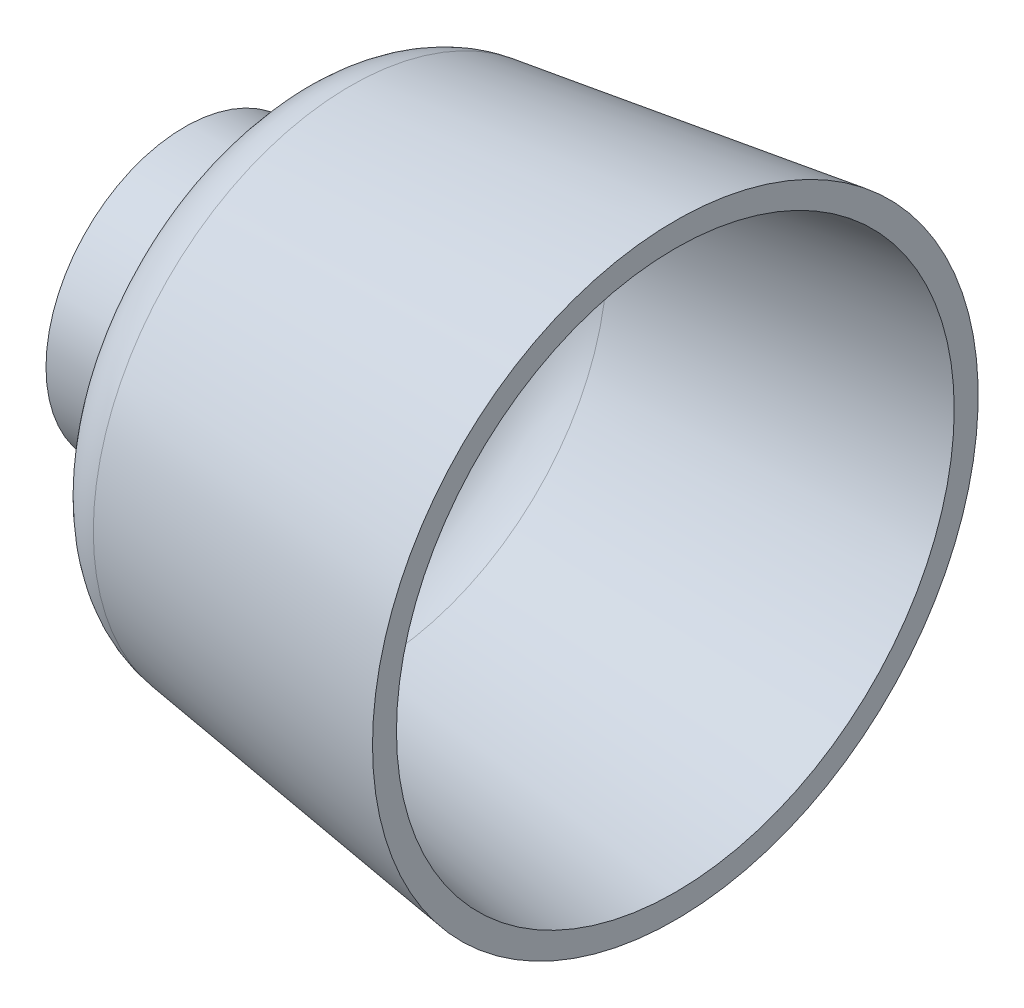
SolidWorks part; units mm, degrees
ref_plane "Front Plane" through (0, 0, 0) normal (0, 0, 1) x (1, 0, 0)
ref_plane "Top Plane" through (0, 0, 0) normal (0, 1, 0) x (1, 0, 0)
ref_plane "Right Plane" through (0, 0, 0) normal (1, 0, 0) x (0, 0, -1)
sketch "Sketch1" plane through (0, 0, 0) normal (0, 0, 1) x (1, 0, 0)
  line L0 (0, 0) -> (59.6872, 0) construction
  line L1 (0, 9.2761) -> (6.35, 9.2761)
  line L2 (6.35, 9.2761) -> (7.6626, 16.7201)
  line L3 (7.6626, 16.7201) -> (32.8154, 20.2551)
  line L4 (0, 9.2761) -> (0, 7.6886)
  line L5 (0, 7.6886) -> (7.6821, 7.6886) construction
  line L6 (7.6821, 7.6886) -> (9.0257, 15.3086)
  line L7 (9.0257, 15.3086) -> (32.8154, 18.652)
  line L8 (32.8154, 20.2551) -> (32.8154, 18.652)
  line L9 (0, 7.6886) -> (0, 0) construction
  line L10 (0, 7.6886) -> (0, 0)
  line L11 (0, 0) -> (7.6821, 0)
  line L12 (7.6821, 0) -> (7.6821, 7.6886)
  dimension "D1" = 7.6886
  dimension "D2" = 6.35
  dimension "D3" = 100
  dimension "D4" = 108
  dimension "D5" = 1.5875
  dimension "D6" = 1.5875
  dimension "D7" = 1.5875
  dimension "D8" = 7.62
  dimension "D9" = 25.4
revolve "Revolve1" add sketch "Sketch1" angle 360 about L0
hole_wizard "Tapped Hole for 9/16-12 Helicoil1" positions "Sketch2" profile "Sketch3" tap size "9/16-12" standard "Helicoil® Inch"
sketch "Sketch2" plane through (0, 0, 0) normal (-1, 0, 0) x (0, 0, 1)
  point P0 (0, 0)
sketch "Sketch3" plane through (0, 0, 0) normal (0, 1, 0) x (0, 0, 1)
  line L0 (0, 0) -> (0, 31.3354)
  line L1 (0, 31.3354) -> (7.3419, 26.924)
  line L2 (7.3419, 26.924) -> (7.3419, 0)
  line L5 (7.3419, 0) -> (0, 0)
  line L10 (0, 31.3354) -> (-7.3419, 26.924) construction
  line L11 (0, -6.35) -> (0, 107.95) construction
  dimension "Tap Drill Dia." = 14.6837
  dimension "Tap Drill Depth" = 26.924
  dimension "Drill Angle" = 118
cosmetic thread "Hole Thread1" parameters "D1"=7.6821, "D2"=17.1475
fillet "Fillet1" radius 4.7625 2 edges at (9.0257, 0, 15.3086) (7.6626, 0, 16.7201)
